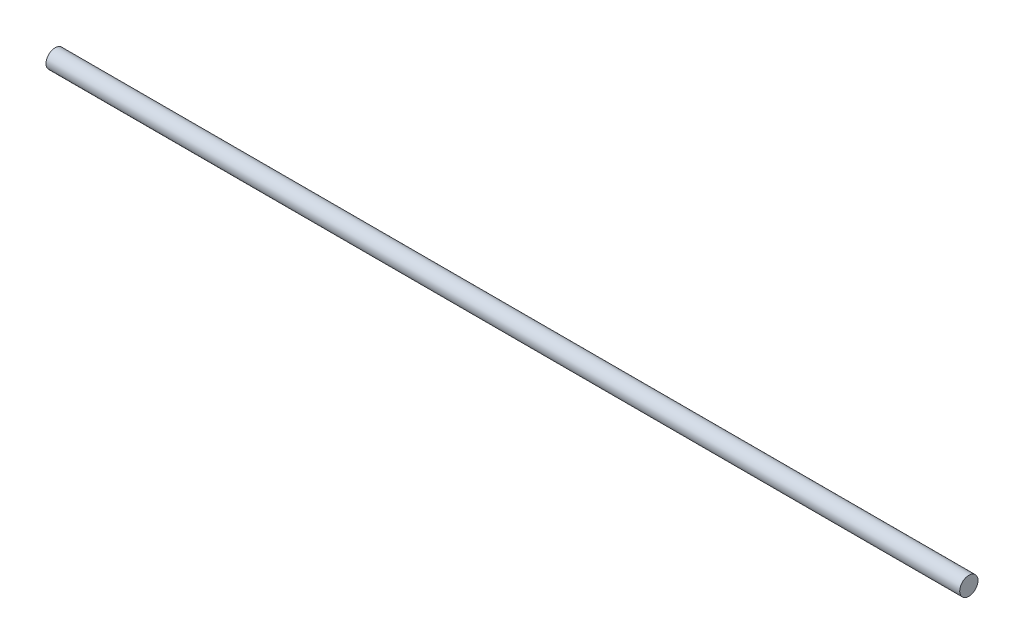
SolidWorks part; units mm, degrees
ref_plane "Front Plane" through (0, 0, 0) normal (0, 0, 1) x (1, 0, 0)
ref_plane "Top Plane" through (0, 0, 0) normal (0, 1, 0) x (1, 0, 0)
ref_plane "Right Plane" through (0, 0, 0) normal (1, 0, 0) x (0, 0, -1)
sketch "Sketch1" plane through (0, 0, 0) normal (1, 0, 0) x (0, 0, -1)
  circle A0 centre (0, 0) radius 4
  dimension "D1" = 8
extrude "Boss-Extrude1" add sketch "Sketch1" along normal blind 400 contours A0
